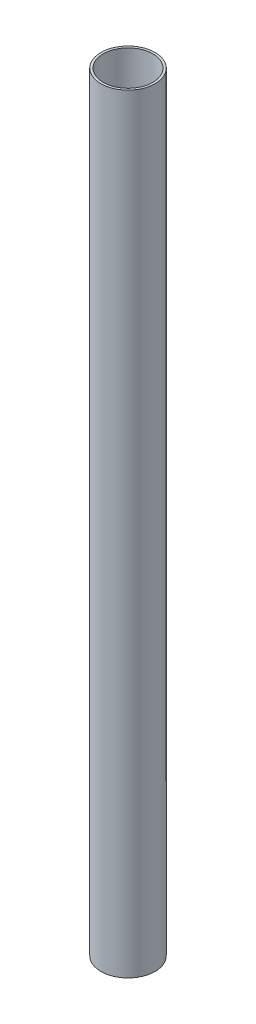
SolidWorks part; units mm, degrees
ref_plane "Front Plane" through (0, 0, 0) normal (0, 0, 1) x (1, 0, 0)
ref_plane "Top Plane" through (0, 0, 0) normal (0, 1, 0) x (1, 0, 0)
ref_plane "Right Plane" through (0, 0, 0) normal (1, 0, 0) x (0, 0, -1)
sketch "Sketch1" plane through (0, 0, 0) normal (0, 1, 0) x (1, 0, 0)
  circle A0 centre (0, 0) radius 15.875
  dimension "D1" = 31.75
extrude "Extrude-Thin1" add sketch "Sketch1" along normal blind 450.85 thin thin type one direction reverse wall 1.3462
